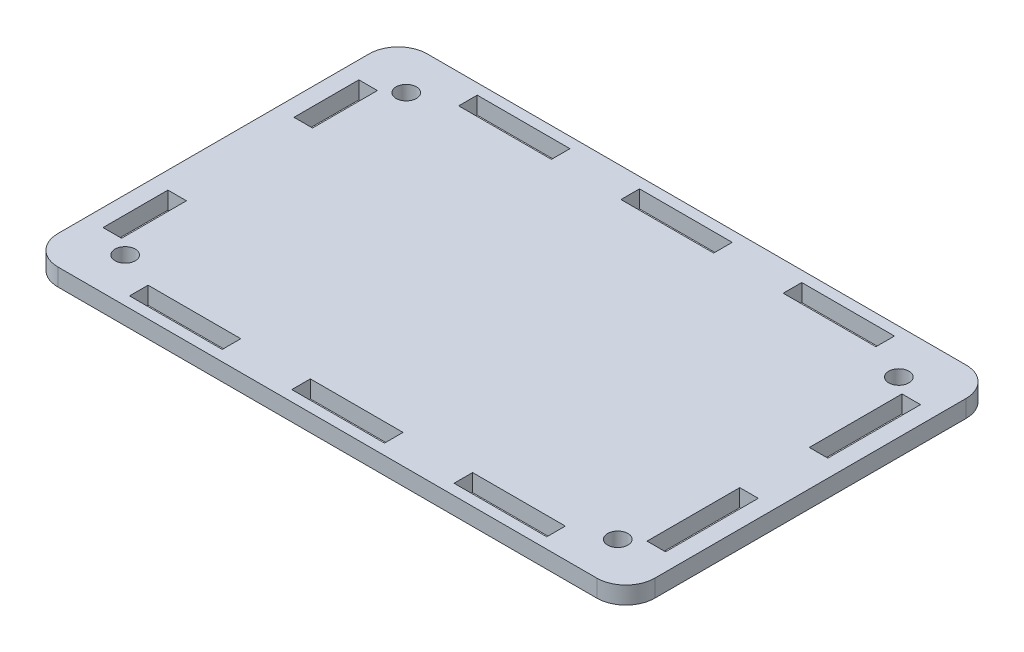
SolidWorks part; units mm, degrees
ref_plane "Front Plane" through (0, 0, 0) normal (0, 0, 1) x (1, 0, 0)
ref_plane "Top Plane" through (0, 0, 0) normal (0, 1, 0) x (1, 0, 0)
ref_plane "Right Plane" through (0, 0, 0) normal (1, 0, 0) x (0, 0, -1)
sketch "Sketch1" plane through (0, 0, 0) normal (0, 1, 0) x (1, 0, 0)
  line L0 (-20, 26.8) -> (-8, 26.8) construction
  line L1 (-51.5, -31.8557) -> (51.5, -31.8557)
  line L2 (-51.5, -31.8557) -> (-51.5, 31.8557)
  line L3 (-51.5, 31.8557) -> (51.5, 31.8557)
  line L4 (51.5, -31.8557) -> (51.5, 31.8557)
  line L5 (-51.5, -31.8557) -> (51.5, 31.8557) construction
  line L6 (-51.5, 31.8557) -> (51.5, -31.8557) construction
  line L7 (-48.5, -30) -> (48.5, -30) construction
  line L8 (-48.5, -30) -> (-48.5, 30) construction
  line L9 (-48.5, 30) -> (48.5, 30) construction
  line L10 (48.5, -30) -> (48.5, 30) construction
  line L11 (-48.5, -30) -> (48.5, 30) construction
  line L12 (-48.5, 30) -> (48.5, -30) construction
  line L13 (-36, 30) -> (-20, 30)
  line L14 (-36, 30) -> (-36, 26.8)
  line L15 (-36, 26.8) -> (-20, 26.8)
  line L16 (-20, 30) -> (-20, 26.8)
  line L17 (20, 30) -> (36, 30)
  line L18 (20, 30) -> (20, 26.8)
  line L19 (20, 26.8) -> (36, 26.8)
  line L20 (36, 30) -> (36, 26.8)
  line L29 (-48.5, 22.075) -> (-45.3, 22.075)
  line L30 (-48.5, 22.075) -> (-48.5, 10.875)
  line L31 (-48.5, 10.875) -> (-45.3, 10.875)
  line L32 (-45.3, 22.075) -> (-45.3, 10.875)
  line L33 (-48.5, -10.875) -> (-45.3, -10.875)
  line L34 (-48.5, -10.875) -> (-48.5, -22.075)
  line L35 (-48.5, -22.075) -> (-45.3, -22.075)
  line L36 (-45.3, -10.875) -> (-45.3, -22.075)
  line L49 (-8, 30) -> (8, 30)
  line L50 (-8, 30) -> (-8, 26.8)
  line L51 (-8, 26.8) -> (8, 26.8)
  line L52 (8, 30) -> (8, 26.8)
  line L53 (8, 26.8) -> (20, 26.8) construction
  line L54 (-45.3, 10.875) -> (-45.3, -10.875) construction
  line L55 (-42.5, 24.25) -> (-42.5, -24.25) construction
  line L56 (-42.5, -24.25) -> (42.5, -24.25) construction
  line L57 (0, 0) -> (0, 26.8) construction
  line L58 (48.5, 0) -> (0, 0) construction
  line L59 (-36, -26.8) -> (-20, -26.8)
  line L60 (-20, -30) -> (-20, -26.8)
  line L61 (-36, -30) -> (-20, -30)
  line L62 (-36, -30) -> (-36, -26.8)
  line L63 (20, -26.8) -> (36, -26.8)
  line L64 (36, -30) -> (36, -26.8)
  line L65 (20, -30) -> (36, -30)
  line L66 (20, -30) -> (20, -26.8)
  line L67 (-8, -26.8) -> (8, -26.8)
  line L68 (8, -30) -> (8, -26.8)
  line L69 (-8, -30) -> (8, -30)
  line L70 (-8, -30) -> (-8, -26.8)
  line L71 (48.5, -22) -> (45.3, -22)
  line L72 (45.3, -6) -> (45.3, -22)
  line L73 (48.5, -6) -> (45.3, -6)
  line L74 (48.5, -6) -> (48.5, -22)
  line L75 (48.5, 6) -> (45.3, 6)
  line L76 (45.3, 22) -> (45.3, 6)
  line L77 (48.5, 22) -> (45.3, 22)
  line L78 (48.5, 22) -> (48.5, 6)
  line L79 (45.3, 6) -> (45.3, -6) construction
  circle A0 centre (-42.5, 24.25) radius 1.75
  circle A1 centre (42.5, 24.25) radius 1.75
  circle A2 centre (-42.5, -24.25) radius 1.75
  circle A3 centre (42.5, -24.25) radius 1.75
  point P0 (0, 0)
  point P5 (0, 0)
  point P19 (-42.5, 0)
  point P20 (0, 26.8)
  point P21 (0, 30)
  point P22 (45.3, 0)
  point P23 (-45.3, 0)
  point P24 (-48.5, 0)
  point P73 (0, -24.25)
  point P74 (0, -31.8557)
  point P75 (-51.5, 0)
  dimension "D1" = 97
  dimension "D6" = 3.5
  dimension "D2" = 103
  dimension "D3" = 60
  dimension "D4" = 85
  dimension "D5" = 48.5
  dimension "D7" = 3.2
  dimension "D8" = 16
  dimension "D9" = 12
  dimension "D10" = 21.75
  dimension "D11" = 11.2
  dimension "D12" = 12
extrude "Boss-Extrude1" add sketch "Sketch1" along normal blind 3
fillet "Fillet1" radius 5 4 edges at (-51.5, 1.5, -31.8557) (51.5, 1.5, -31.8557) (51.5, 1.5, 31.8557) (-51.5, 1.5, 31.8557)
